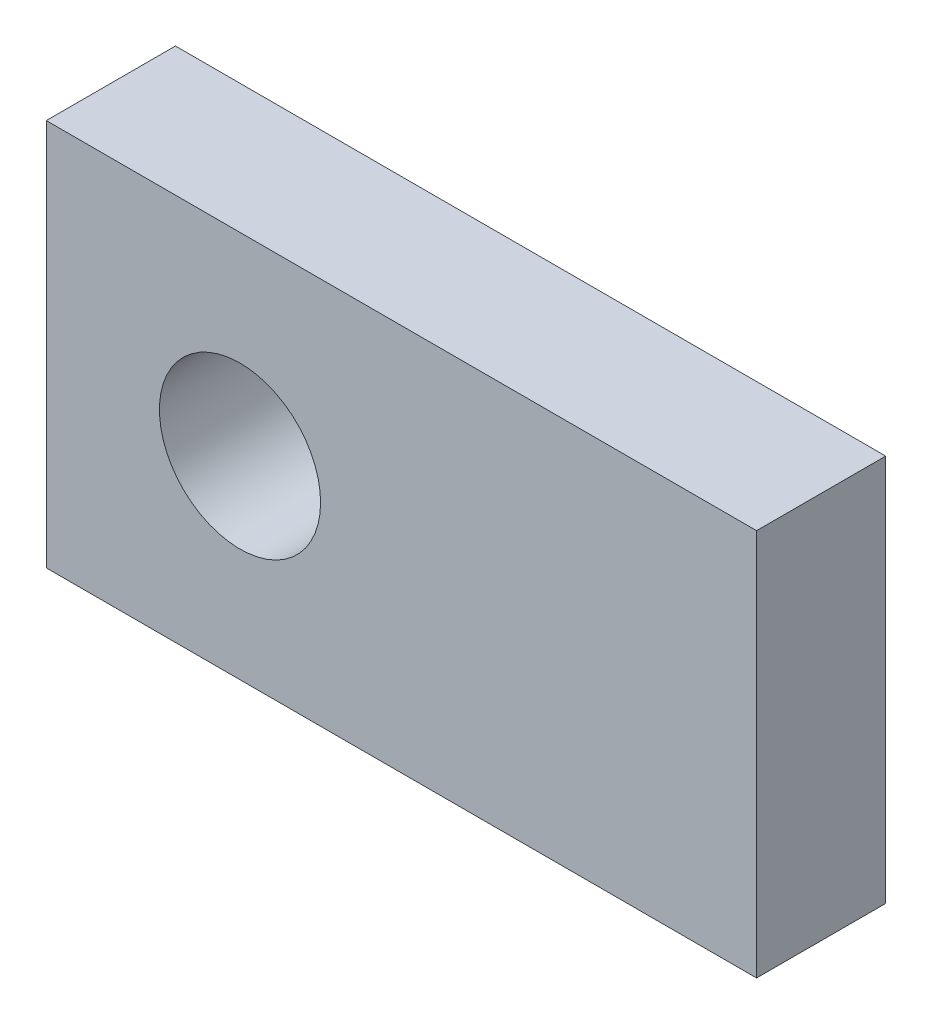
SolidWorks part; units mm, degrees
ref_plane "Front Plane" through (0, 0, 0) normal (0, 0, 1) x (1, 0, 0)
ref_plane "Top Plane" through (0, 0, 0) normal (0, 1, 0) x (1, 0, 0)
ref_plane "Right Plane" through (0, 0, 0) normal (1, 0, 0) x (0, 0, -1)
sketch "Sketch1" plane through (0, 0, 0) normal (0, 0, 1) x (1, 0, 0)
  line L0 (0, 0) -> (0, 32866.8508) construction
  line L2 (-17.4625, -9.525) -> (17.4625, -9.525)
  line L3 (-17.4625, -9.525) -> (-17.4625, 9.525)
  line L4 (-17.4625, 9.525) -> (17.4625, 9.525)
  line L5 (17.4625, -9.525) -> (17.4625, 9.525)
  line L6 (-17.4625, -9.525) -> (17.4625, 9.525) construction
  line L7 (-17.4625, 9.525) -> (17.4625, -9.525) construction
  circle A0 centre (-7.9375, 0) radius 3.9624
  point P3 (0, 0)
  dimension "D1" = 7.9248
  dimension "D2" = 34.925
  dimension "D3" = 19.05
  dimension "D4" = 9.525
  dimension "D5" = 9.525
extrude "Boss-Extrude1" add sketch "Sketch1" along normal blind 6.35
